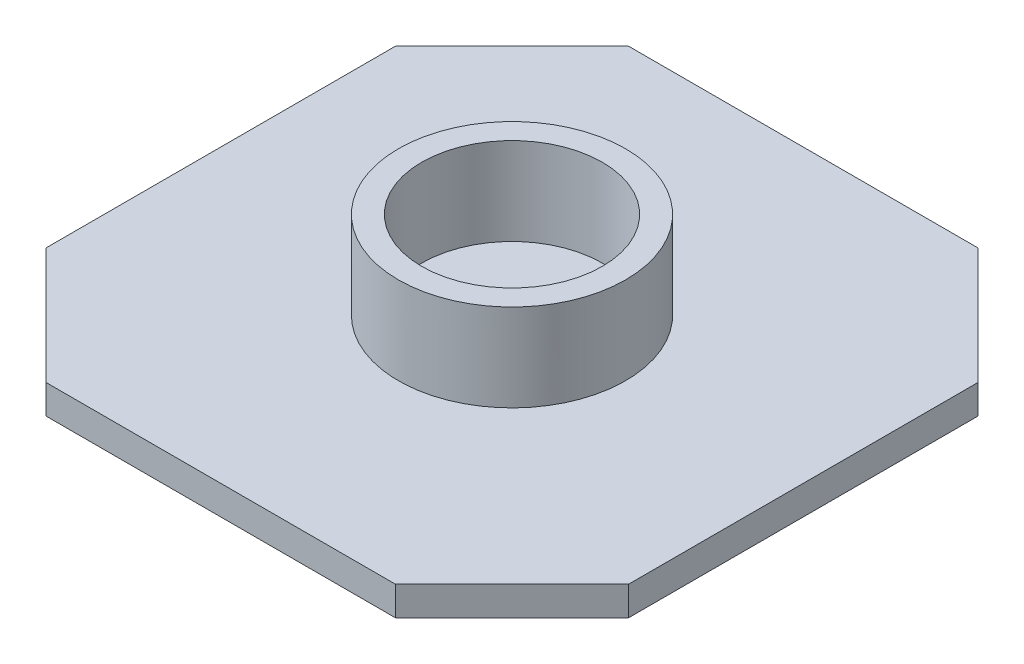
SolidWorks part; units mm, degrees
ref_plane "Ebene vorne" through (0, 0, 0) normal (0, 0, 1) x (1, 0, 0)
ref_plane "Ebene oben" through (0, 0, 0) normal (0, 1, 0) x (1, 0, 0)
ref_plane "Ebene rechts" through (0, 0, 0) normal (1, 0, 0) x (0, 0, -1)
sketch "Skizze1" plane through (0, 0, 0) normal (0, 1, 0) x (1, 0, 0)
  line L1 (-10, -10) -> (10, -10)
  line L2 (-10, -10) -> (-10, 10)
  line L3 (-10, 10) -> (10, 10)
  line L4 (10, -10) -> (10, 10)
  line L5 (-10, -10) -> (10, 10) construction
  line L6 (-10, 10) -> (10, -10) construction
  point P0 (0, 0)
  dimension "D1" = 20
extrude "Aufsatz-Linear austragen1" add sketch "Skizze1" along normal blind 1
sketch "Skizze2" plane through (0, 1, 0) normal (0, 1, 0) x (1, 0, 0)
  circle A0 centre (0, 0) radius 3.9
  circle A1 centre (0, 0) radius 3.1
  dimension "D1" = 6.2
  dimension "D2" = 0.8
extrude "Aufsatz-Linear austragen2" add sketch "Skizze2" along normal blind 3
chamfer "Fase1" distance 4 angle 45 4 edges at (-10, 0.5, -10) (10, 0.5, -10) (10, 0.5, 10) (-10, 0.5, 10)
